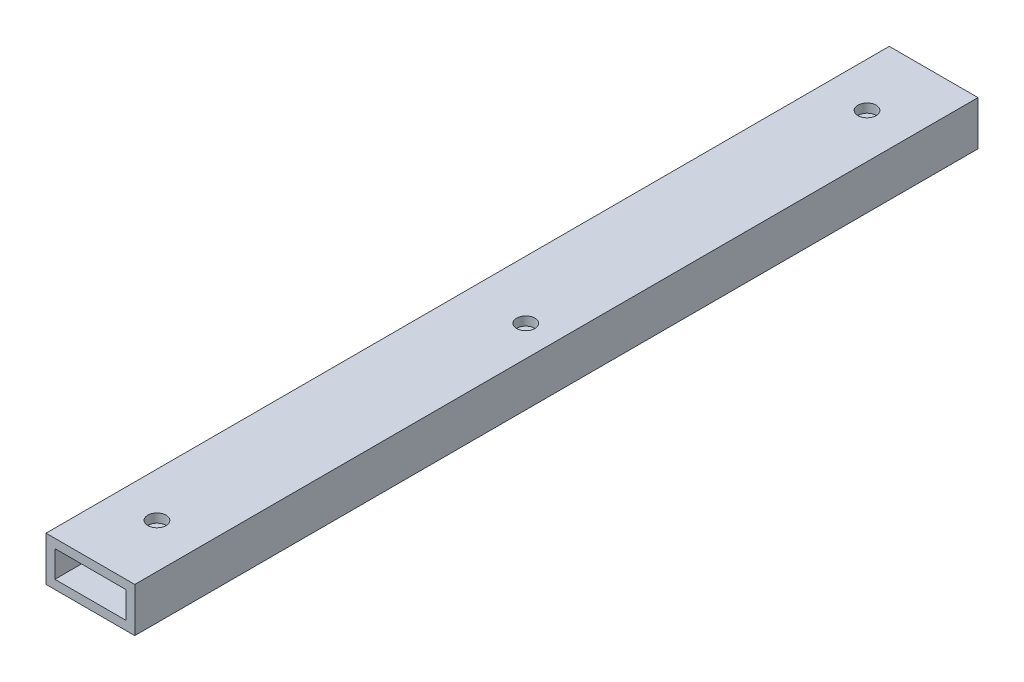
SolidWorks part; units mm, degrees
material "6063-T1"
ref_plane "前视基准面" through (0, 0, 0) normal (0, 0, 1) x (1, 0, 0)
ref_plane "上视基准面" through (0, 0, 0) normal (0, 1, 0) x (1, 0, 0)
ref_plane "右视基准面" through (0, 0, 0) normal (1, 0, 0) x (0, 0, -1)
other "Configuration Table"
sketch "草图1" plane through (0, 0, 0) normal (0, 0, 1) x (1, 0, 0)
  line L1 (-9.9632, 5.0382) -> (10.0368, 5.0382)
  line L2 (-9.9632, 5.0382) -> (-9.9632, -4.9618)
  line L3 (-9.9632, -4.9618) -> (10.0368, -4.9618)
  line L4 (10.0368, 5.0382) -> (10.0368, -4.9618)
  line L7 (-7.9632, 3.0382) -> (8.0368, 3.0382)
  line L8 (-7.9632, 3.0382) -> (-7.9632, -2.9618)
  line L9 (-7.9632, -2.9618) -> (8.0368, -2.9618)
  line L10 (8.0368, 3.0382) -> (8.0368, -2.9618)
  line L11 (-7.9632, 3.0382) -> (8.0368, -2.9618) construction
  line L12 (-7.9632, -2.9618) -> (8.0368, 3.0382) construction
  point P0 (0, 0)
  point P6 (0.0368, 0.0382)
  dimension "D1" = 20
  dimension "D2" = 10
  dimension "D3" = 2
  dimension "D4" = 2
  dimension "D5" = 2
  dimension "D6" = 2
extrude "凸台-拉伸1" add sketch "草图1" along normal mid plane 190
sketch "草图2" plane through (0, 5.0382, 0) normal (0, 1, 0) x (1, 0, 0)
  line L0 (0, 77) -> (0, 52) construction
  line L1 (5, 77) -> (5, 52)
  line L2 (-5, 77) -> (-5, 52)
  line L3 (10.0368, 95) -> (-9.9632, 95) construction
  arc A0 (5, 77) -> (-5, 77) centre (0, 77) ccw
  arc A1 (-5, 52) -> (5, 52) centre (0, 52) ccw
  point P3 (0, 64.5)
  dimension "D1" = 5
  dimension "D2" = 25
  dimension "D3" = 18
ref_plane "基准面1" through (0, 0, 0) normal (0, 0, 1) x (1, 0, 0)
sketch "草图3" plane through (0, 5.0382, 0) normal (0, 1, 0) x (1, 0, 0)
  line L0 (-5.5, 0) -> (5.5, 0) construction
  line L1 (-9.9632, -95) -> (-9.9632, 95) construction
  line L4 (0.0368, -95) -> (0.0368, -86.7853) construction
  line L5 (10.0368, -95) -> (-9.9632, -95) construction
  line L6 (10.0368, 95) -> (-9.9632, 95) construction
  circle A0 centre (3.1368, 0) radius 2.05
  circle A1 centre (0.0368, 80) radius 2.05
  circle A2 centre (0.0368, -80) radius 2.05
  dimension "D1" = 4.1
  dimension "D3" = 4.1
  dimension "D5" = 4.1
  dimension "D2" = 13.1
  dimension "D4" = 15
extrude "切除-拉伸1" cut sketch "草图3" against normal through all
